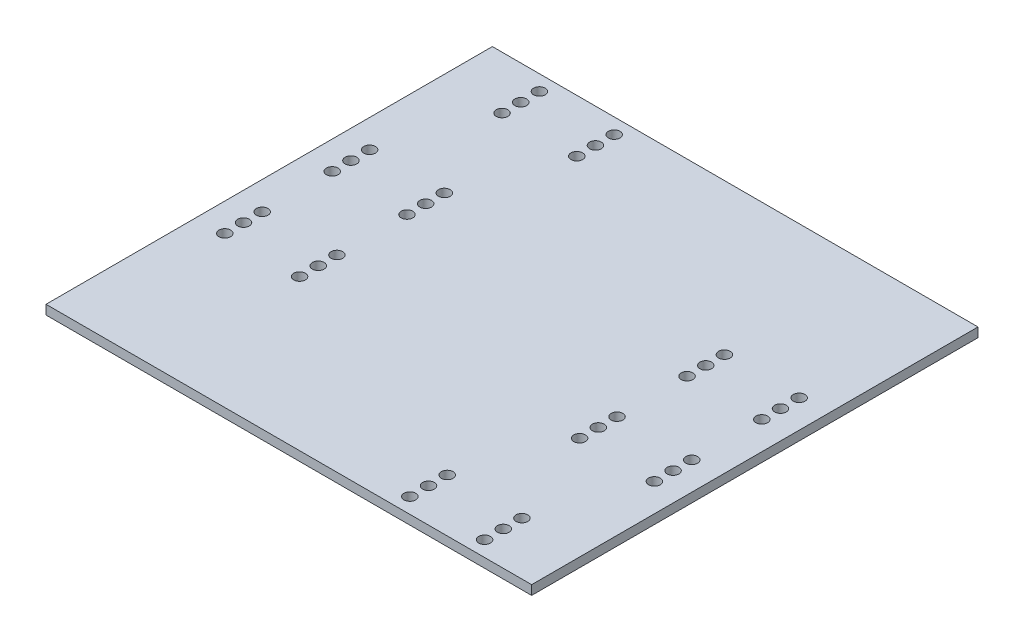
SolidWorks part; units mm, degrees
ref_plane "Alzado" through (0, 0, 0) normal (0, 0, 1) x (1, 0, 0)
ref_plane "Planta" through (0, 0, 0) normal (0, 1, 0) x (1, 0, 0)
ref_plane "Vista lateral" through (0, 0, 0) normal (1, 0, 0) x (0, 0, -1)
sketch "Croquis1" plane through (0, 0, 0) normal (0, 1, 0) x (1, 0, 0)
  line L1 (165, -151.655) -> (-165, -151.655)
  line L2 (165, -151.655) -> (165, 151.655)
  line L3 (165, 151.655) -> (-165, 151.655)
  line L4 (-165, -151.655) -> (-165, 151.655)
  line L5 (165, -151.655) -> (-165, 151.655) construction
  line L6 (165, 151.655) -> (-165, -151.655) construction
  point P0 (0, 0)
  dimension "D1" = 330
  dimension "D2" = 303.31
extrude "Saliente-Extruir2" add sketch "Croquis1" along normal blind 6.35
sketch "Croquis2" plane through (0, 6.35, 0) normal (0, 1, 0) x (1, 0, 0)
  line L0 (-165, 129.3909) -> (165, 129.3909) construction
  line L3 (-165, 151.655) -> (-165, -151.655) construction
  line L4 (165, -151.655) -> (165, 151.655) construction
sketch "Croquis3" plane through (0, 6.35, 0) normal (0, 1, 0) x (1, 0, 0)
  line L0 (-165, -151.655) -> (165, -151.655) construction
  line L1 (-165, 151.655) -> (-135.28, 151.655)
  line L2 (-165, 151.655) -> (-165, -151.655)
  line L3 (-165, -151.655) -> (-135.28, -151.655)
  line L4 (-135.28, 151.655) -> (-135.28, -151.655)
  line L5 (-165, -118.245) -> (165, -118.245) construction
  line L6 (165, -151.655) -> (165, 151.655) construction
  line L7 (-122.58, -147.8926) -> (-122.58, -88.5974) construction
  line L8 (-97.18, -151.655) -> (-97.18, -77.7371) construction
  line L9 (0, 151.655) -> (0, -151.655) construction
  line L10 (165, 151.655) -> (-165, 151.655) construction
  line L11 (-165, 0) -> (165, 0) construction
  circle A0 centre (-122.58, -118.245) radius 3.9687
  circle A1 centre (-122.58, -105.545) radius 3.9687
  circle A2 centre (-122.58, -130.945) radius 3.9687
  circle A3 centre (-71.78, -130.945) radius 3.9687
  circle A4 centre (-71.78, -118.245) radius 3.9687
  circle A5 centre (-71.78, -105.545) radius 3.9687
  circle A24 centre (122.58, 118.245) radius 3.9687
  circle A25 centre (122.58, 105.545) radius 3.9687
  circle A26 centre (122.58, 130.945) radius 3.9687
  circle A27 centre (71.78, 130.945) radius 3.9687
  circle A28 centre (71.78, 118.245) radius 3.9687
  circle A29 centre (71.78, 105.545) radius 3.9687
  point P16 (-122.58, -118.245)
  point P59 (122.58, 118.245)
  dimension "D3" = 12.7
  dimension "D4" = 7.9375
  dimension "D5" = 12.7
  dimension "D6" = 12.7
  dimension "D1" = 29.72
  dimension "D2" = 33.41
  dimension "D7" = 25.4
sketch "Croquis4" plane through (0, 6.35, 0) normal (0, 1, 0) x (1, 0, 0)
  line L0 (0, 151.655) -> (0, -151.655) construction
  line L1 (165, 151.655) -> (-165, 151.655) construction
  line L2 (-165, -151.655) -> (165, -151.655) construction
  line L3 (-158.65, 151.655) -> (-158.65, -151.655) construction
  line L4 (-165, 151.655) -> (-165, -151.655) construction
  line L5 (158.65, 151.655) -> (158.65, -151.655) construction
  line L6 (0, -159.495) -> (270.56, -159.495) construction
  line L7 (135.28, -159.495) -> (135.28, -97.519) construction
  line L8 (122.58, -159.495) -> (122.58, -97.519) construction
  line L9 (122.58, -128.507) -> (158.65, -128.507) construction
  line L10 (97.18, -159.495) -> (97.18, -97.519) construction
  line L11 (82.45, -36.499) -> (158.65, -36.499) construction
  line L12 (135.28, -97.519) -> (59.08, -97.519) construction
  line L13 (135.28, -97.519) -> (135.28, -159.495) construction
  line L14 (135.28, -159.495) -> (59.08, -159.495) construction
  line L15 (59.08, -97.519) -> (59.08, -159.495) construction
  line L16 (158.65, -5.509) -> (82.45, -5.509) construction
  line L17 (158.65, -5.509) -> (158.65, -67.489) construction
  line L18 (158.65, -67.489) -> (82.45, -67.489) construction
  line L19 (82.45, -5.509) -> (82.45, -67.489) construction
  line L20 (120.55, -5.509) -> (120.55, -67.489) construction
  line L21 (95.15, -5.509) -> (95.15, -67.489) construction
  line L22 (165, 0) -> (-165, 0) construction
  line L23 (165, -151.655) -> (165, 151.655) construction
  circle A1 centre (122.58, -128.507) radius 3.9688
  circle A2 centre (122.58, -115.807) radius 3.9688
  circle A3 centre (122.58, -141.207) radius 3.9688
  circle A4 centre (71.78, -141.207) radius 3.9688
  circle A5 centre (71.78, -128.507) radius 3.9688
  circle A6 centre (71.78, -115.807) radius 3.9688
  circle A7 centre (95.15, -36.499) radius 3.9688
  circle A8 centre (95.15, -23.799) radius 3.9688
  circle A9 centre (95.15, -49.199) radius 3.9688
  circle A10 centre (145.95, -49.199) radius 3.9688
  circle A11 centre (145.95, -36.499) radius 3.9688
  circle A12 centre (145.95, -23.799) radius 3.9688
  circle A19 centre (145.95, 49.199) radius 3.9687
  circle A20 centre (95.15, 49.199) radius 3.9688
  circle A21 centre (145.95, 36.499) radius 3.9688
  circle A22 centre (95.15, 36.499) radius 3.9688
  circle A23 centre (145.95, 23.799) radius 3.9688
  circle A24 centre (95.15, 23.799) radius 3.9688
  circle A31 centre (-95.15, -49.199) radius 3.9688
  circle A32 centre (-145.95, -49.199) radius 3.9688
  circle A33 centre (-145.95, -36.499) radius 3.9688
  circle A34 centre (-95.15, -36.499) radius 3.9688
  circle A35 centre (-95.15, -23.799) radius 3.9688
  circle A36 centre (-145.95, -23.799) radius 3.9688
  circle A37 centre (-145.95, 49.199) radius 3.9687
  circle A38 centre (-145.95, 36.499) radius 3.9688
  circle A39 centre (-145.95, 23.799) radius 3.9688
  circle A40 centre (-95.15, 23.799) radius 3.9688
  circle A41 centre (-95.15, 36.499) radius 3.9688
  circle A42 centre (-95.15, 49.199) radius 3.9688
  circle A43 centre (-122.58, 115.807) radius 3.9687
  circle A44 centre (-122.58, 128.507) radius 3.9687
  circle A45 centre (-122.58, 141.207) radius 3.9687
  circle A46 centre (-71.78, 115.807) radius 3.9688
  circle A47 centre (-71.78, 128.507) radius 3.9688
  circle A48 centre (-71.78, 141.207) radius 3.9688
  dimension "D7" = 7.9375
  dimension "D8" = 12.7
  dimension "D10" = 0
  dimension "D15" = 7.9375
  dimension "D16" = 12.7
  dimension "D1" = 6.35
  dimension "D2" = 7.84
  dimension "D3" = 23.37
  dimension "D4" = 12.7
  dimension "D5" = 61.976
  dimension "D6" = 0
  dimension "D9" = 25.4
  dimension "D11" = 76.2
  dimension "D12" = 61.98
  dimension "D13" = 76.2
  dimension "D14" = 12.7
  dimension "D17" = 30.03
extrude "Cortar-Extruir1" cut sketch "Croquis4" against normal blind 10
